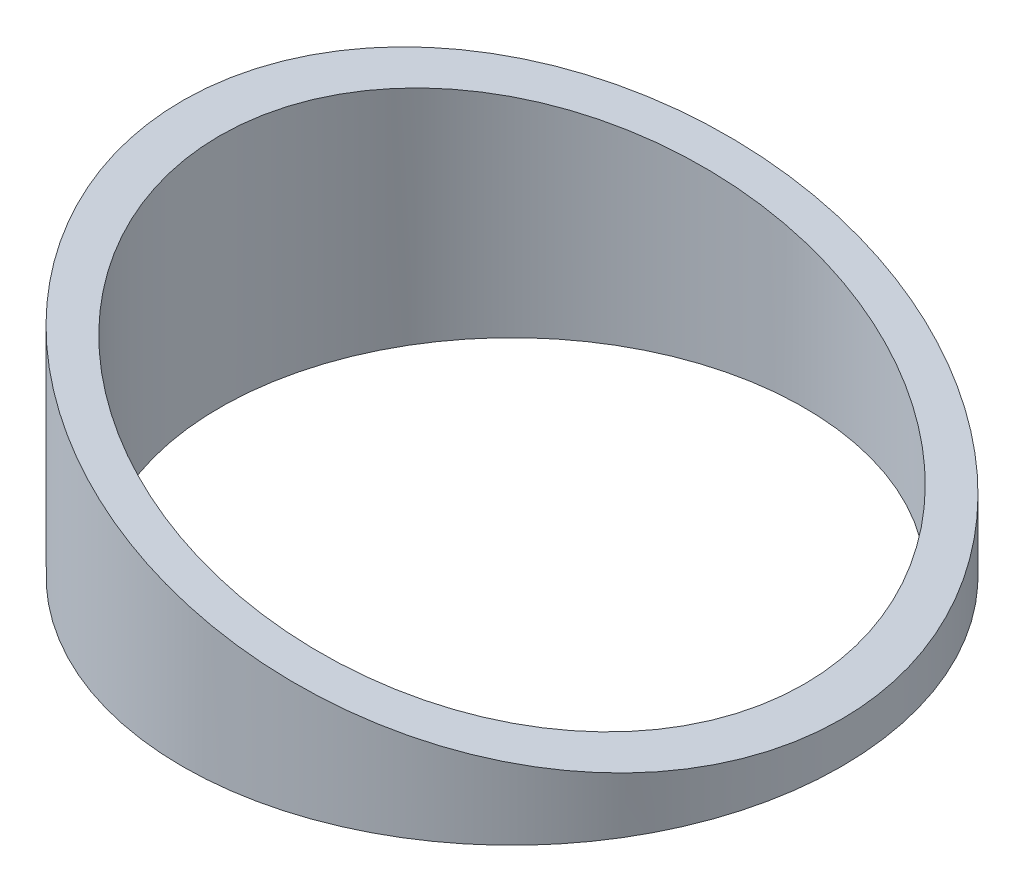
SolidWorks part; units mm, degrees
ref_plane "Front Plane" through (0, 0, 0) normal (0, 0, 1) x (1, 0, 0)
ref_plane "Top Plane" through (0, 0, 0) normal (0, 1, 0) x (1, 0, 0)
ref_plane "Right Plane" through (0, 0, 0) normal (1, 0, 0) x (0, 0, -1)
sketch "Sketch1" plane through (0, 0, 0) normal (0, 1, 0) x (1, 0, 0)
  circle A0 centre (0, 0) radius 26.5
  circle A1 centre (0, 0) radius 23.5
  dimension "D1" = 53
  dimension "D2" = 3
extrude "Boss-Extrude1" add sketch "Sketch1" along normal blind 20
sketch "Sketch2" plane through (0, 0, 0) normal (0, 0, 1) x (1, 0, 0)
  line L0 (29.1336, 2.4719) -> (-28.9607, 20.6441)
  line L3 (-28.9607, 20.6441) -> (-26.1356, 26.7051)
  line L4 (-26.1356, 26.7051) -> (41.765, 26.1713)
  line L5 (41.765, 26.1713) -> (29.1336, 2.4719)
extrude "Cut-Extrude1" cut sketch "Sketch2" against normal through all both and the other way through all
equation "\"D1@Sketch1\"=47+6"
